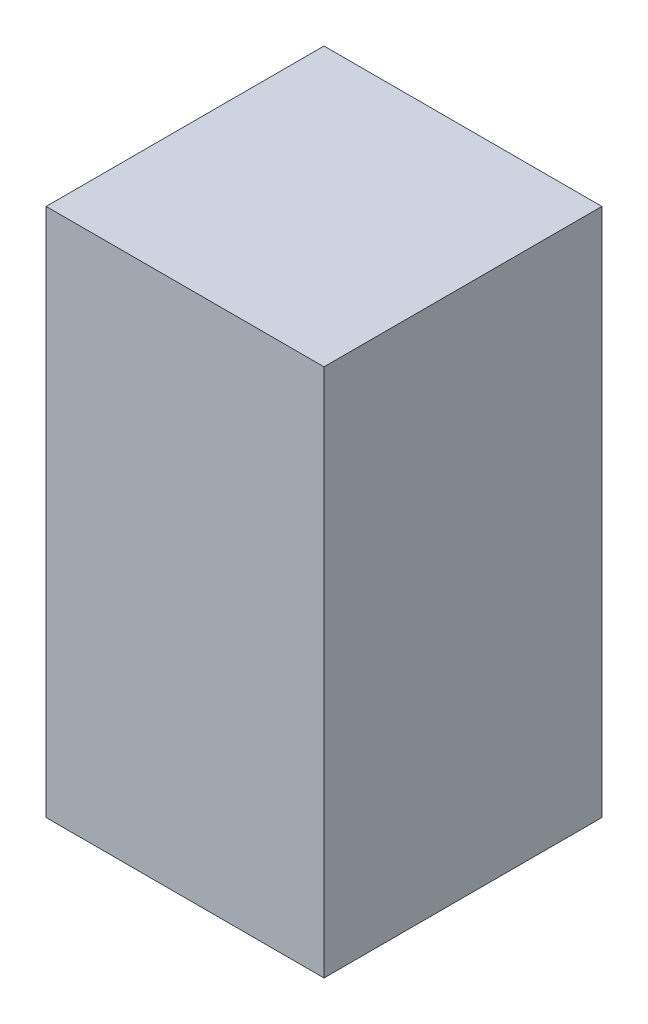
SolidWorks part; units mm, degrees
ref_plane "Front Plane" through (0, 0, 0) normal (0, 0, 1) x (1, 0, 0)
ref_plane "Top Plane" through (0, 0, 0) normal (0, 1, 0) x (1, 0, 0)
ref_plane "Right Plane" through (0, 0, 0) normal (1, 0, 0) x (0, 0, -1)
sketch "Sketch1" plane through (0, 0, 0) normal (0, 1, 0) x (1, 0, 0)
  line L1 (0, -58.2549) -> (0, 58.2549) construction
  line L5 (-58.2549, 0) -> (58.2549, 0) construction
  line L6 (0, 80) -> (-80, 80)
  line L7 (-80, 80) -> (-80, 0)
  line L8 (-80, 0) -> (-80, -80)
  line L9 (-80, -80) -> (0, -80)
  line L10 (80, 0) -> (80, -80)
  line L11 (80, -80) -> (0, -80)
  line L12 (80, 0) -> (80, 80)
  line L13 (80, 80) -> (0, 80)
  circle A0 centre (0, 0) radius 72.136
  point P16 (-80, 0)
  point P17 (0, 80)
  point P18 (80, 0)
  point P19 (0, -80)
extrude "Boss-Extrude1" add sketch "Sketch1" along normal blind 304.8 contours L8 L9 L11 L10 L12 L13 L6 L7
sketch "Sketch3" plane through (0, 304.8, 0) normal (0, 1, 0) x (1, 0, 0)
  circle A0 centre (0, 0) radius 61.468
  dimension "D1" = 122.936
